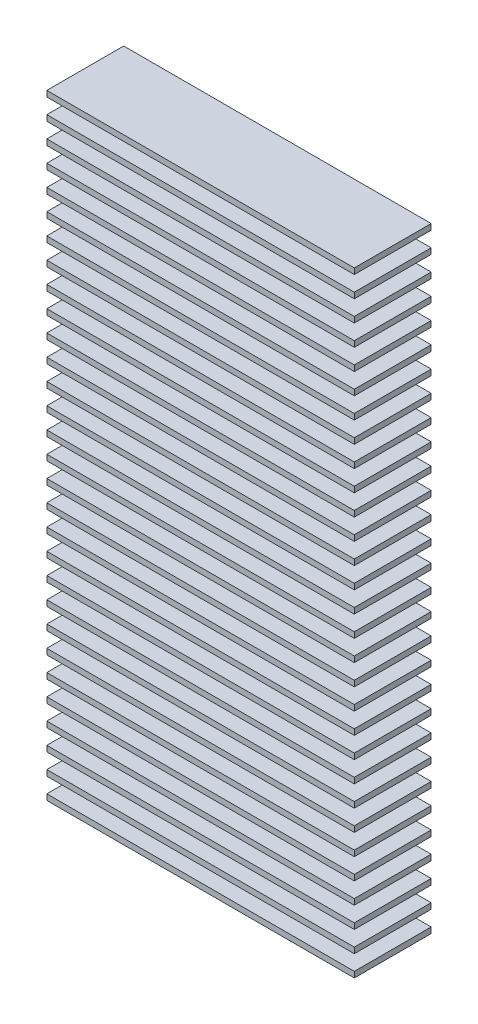
SolidWorks part; units mm, degrees
other "Markup1"
sketch "Sketch13" plane through (-145, 20, -80) normal (-0.546, 0.1848, -0.8171) x (-0.8337, -0.0238, 0.5517)
ref_plane "Front Plane" through (0, 0, 0) normal (0, 0, 1) x (1, 0, 0)
ref_plane "Top Plane" through (0, 0, 0) normal (0, 1, 0) x (1, 0, 0)
ref_plane "Right Plane" through (0, 0, 0) normal (1, 0, 0) x (0, 0, -1)
sketch "Sketch14" plane through (0, 0, 0) normal (0, 1, 0) x (1, 0, 0)
  line L0 (0, 32.1052) -> (0, -48.8567) construction
  circle A0 centre (-40, 0) radius 5
  circle A1 centre (40, 0) radius 5
  dimension "D1" = 10
  dimension "D2" = 10
  dimension "D3" = 80
extrude "Boss-Extrude1" add sketch "Sketch14" along normal mid plane 320
sketch "Sketch15" plane through (0, 160, 0) normal (0, 1, 0) x (1, 0, 0)
  line L1 (-80, 20) -> (80, 20)
  line L2 (-80, 20) -> (-80, -20)
  line L3 (-80, -20) -> (80, -20)
  line L4 (80, 20) -> (80, -20)
  circle A0 centre (40, 0) radius 5 construction
  dimension "D1" = 20
  dimension "D2" = 20
  dimension "D3" = 40
  dimension "D4" = 160
extrude "Boss-Extrude2" add sketch "Sketch15" against normal blind 3
pattern_linear "LPattern1" count 30 spacing 10.931 along (0, -1, 0) of "Boss-Extrude2"
